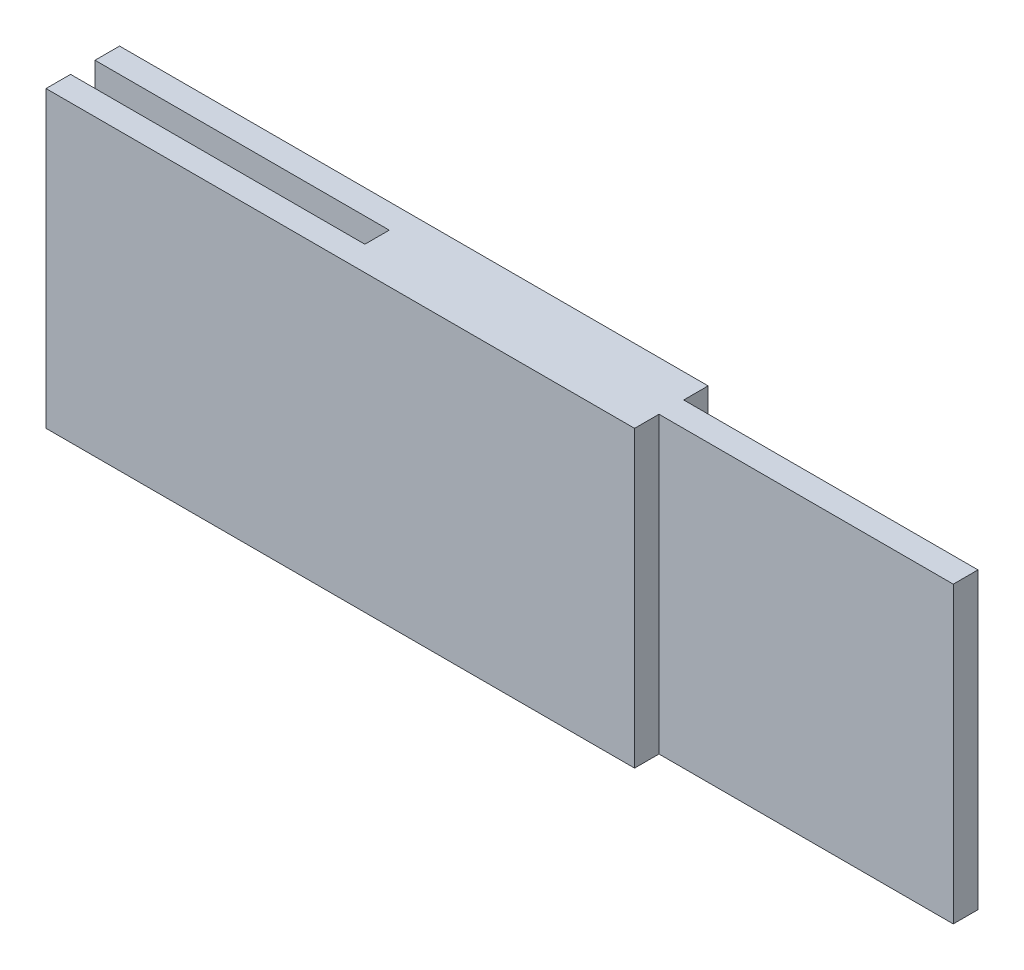
SolidWorks part; units mm, degrees
ref_plane "Front Plane" through (0, 0, 0) normal (0, 0, 1) x (1, 0, 0)
ref_plane "Top Plane" through (0, 0, 0) normal (0, 1, 0) x (1, 0, 0)
ref_plane "Right Plane" through (0, 0, 0) normal (1, 0, 0) x (0, 0, -1)
sketch "Sketch1" plane through (0, 0, 0) normal (0, 0, 1) x (1, 0, 0)
  line L1 (30, -10) -> (-30, -10)
  line L2 (30, -10) -> (30, 10)
  line L3 (30, 10) -> (-30, 10)
  line L4 (-30, -10) -> (-30, 10)
  line L5 (30, -10) -> (-30, 10) construction
  line L6 (30, 10) -> (-30, -10) construction
  point P0 (0, 0)
  dimension "D1" = 20
  dimension "D2" = 60
extrude "Boss-Extrude1" add sketch "Sketch1" along normal mid plane 5
sketch "Sketch2" plane through (0, 10, 0) normal (0, 1, 0) x (1, 0, 0)
  line L0 (-30, -2.5) -> (-30, 2.5) construction
  line L1 (-30, 0.83) -> (-10, 0.83)
  line L2 (-30, 0.83) -> (-30, -0.83)
  line L3 (-30, -0.83) -> (-10, -0.83)
  line L4 (-10, 0.83) -> (-10, -0.83)
  line L5 (-10, 0) -> (0, 0) construction
  line L7 (30, 2.5) -> (10, 2.5)
  line L8 (30, 2.5) -> (30, 0.84)
  line L9 (30, 0.84) -> (10, 0.84)
  line L10 (10, 2.5) -> (10, 0.84)
  line L11 (30, -2.5) -> (10, -2.5)
  line L12 (30, -2.5) -> (30, -0.84)
  line L13 (30, -0.84) -> (10, -0.84)
  line L14 (10, -2.5) -> (10, -0.84)
  dimension "D1" = 1.66
  dimension "D2" = 20
extrude "Cut-Extrude1" cut sketch "Sketch2" against normal through all
